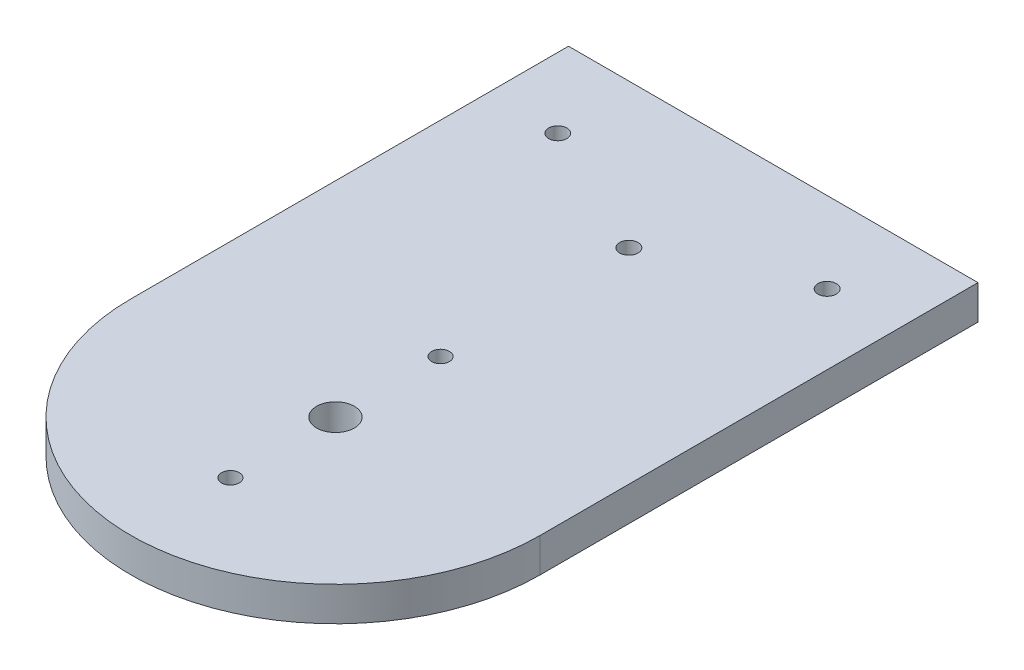
SolidWorks part; units mm, degrees
material "Aleación 6061"
ref_plane "Alzado" through (0, 0, 0) normal (0, 0, 1) x (1, 0, 0)
ref_plane "Planta" through (0, 0, 0) normal (0, 1, 0) x (1, 0, 0)
ref_plane "Vista lateral" through (0, 0, 0) normal (1, 0, 0) x (0, 0, -1)
sketch "Croquis1" plane through (0, 0, 0) normal (0, 1, 0) x (1, 0, 0)
  line L1 (-38, -90.2) -> (38, -90.2)
  line L2 (-38, -90.2) -> (-38, -171.45)
  line L3 (-38, -171.45) -> (38, -171.45)
  line L4 (38, -90.2) -> (38, -171.45)
  dimension "D1" = 38
  dimension "D2" = 90.2
  dimension "D3" = 38
  dimension "D4" = 90.2
  dimension "D5" = 38
  dimension "D6" = 171.45
  dimension "D7" = 38
  dimension "D8" = 171.45
extrude "Pared_B_chumacera_J2" add sketch "Croquis1" along normal blind 6.35 from offset 21.35
sketch "Croquis2" plane through (0, 0, 0) normal (0, 1, 0) x (1, 0, 0)
  circle A0 centre (0, -171.45) radius 38
  dimension "D1" = 76
  dimension "D2" = 171.45
extrude "Pared_B_chumacera_J2_redondeo" add sketch "Croquis2" along normal blind 6.35 from offset 21.35
sketch "Croquis3" plane through (0, 0, 0) normal (0, 1, 0) x (1, 0, 0)
  circle A0 centre (0, -171.45) radius 3.5
  circle A1 centre (0, -190.95) radius 1.65
  circle A2 centre (0, -151.95) radius 1.65
  dimension "D1" = 7
  dimension "D2" = 3.3
  dimension "D3" = 3.3
  dimension "D4" = 171.45
  dimension "D5" = 190.95
  dimension "D6" = 151.95
extrude "Paso_pin_y_rosca_M4_ejefalso" cut sketch "Croquis3" along normal blind 6.35 from offset 21.35
sketch "Croquis4" plane through (0, 0, 0) normal (0, 1, 0) x (1, 0, 0)
  circle A0 centre (-25, -105.2) radius 1.25
  circle A1 centre (25, -105.2) radius 1.25
  dimension "D1" = 2.5
  dimension "D2" = 2.5
  dimension "D3" = 25
  dimension "D4" = 105.2
  dimension "D5" = 25
  dimension "D6" = 105.2
extrude "Rosca_M3_escuadras" cut sketch "Croquis4" along normal blind 6.35 from offset 21.35
sketch "Croquis5" plane through (0, 0, 0) normal (0, 0, 1) x (1, 0, 0)
  circle A0 centre (-30, -18.175) radius 2
  circle A1 centre (30, -18.175) radius 2
  dimension "D1" = 4
  dimension "D2" = 4
  dimension "D3" = 30
  dimension "D4" = 18.175
  dimension "D5" = 30
  dimension "D6" = 18.175
extrude "Pasadores_D4" cut sketch "Croquis5" along normal blind 8 from offset 90.2
sketch "Croquis6" plane through (0, 0, 0) normal (0, 1, 0) x (1, 0, 0)
  circle A0 centre (0, -117) radius 1.25
  dimension "D1" = 2.5
  dimension "D2" = 117
extrude "Rosca_M3_bases_cincho" cut sketch "Croquis6" along normal blind 6.35 from offset 21.35
sketch "Croquis7" plane through (0, 0, 0) normal (0, 1, 0) x (1, 0, 0)
  circle A0 centre (-25, -105.2) radius 1.7
  circle A1 centre (25, -105.2) radius 1.7
  dimension "D1" = 3.4
  dimension "D2" = 3.4
  dimension "D3" = 25
  dimension "D4" = 105.2
  dimension "D5" = 25
  dimension "D6" = 105.2
extrude "Paso_M3_escuadras_tuerca" cut sketch "Croquis7" along normal blind 6.35 from offset 21.35
sketch "Croquis8" plane through (0, 0, 0) normal (0, 1, 0) x (1, 0, 0)
  circle A0 centre (0, -117) radius 1.7
  dimension "D1" = 3.4
  dimension "D2" = 117
extrude "Paso_M3_base_cincho_tuerca" cut sketch "Croquis8" along normal blind 6.35 from offset 21.35
